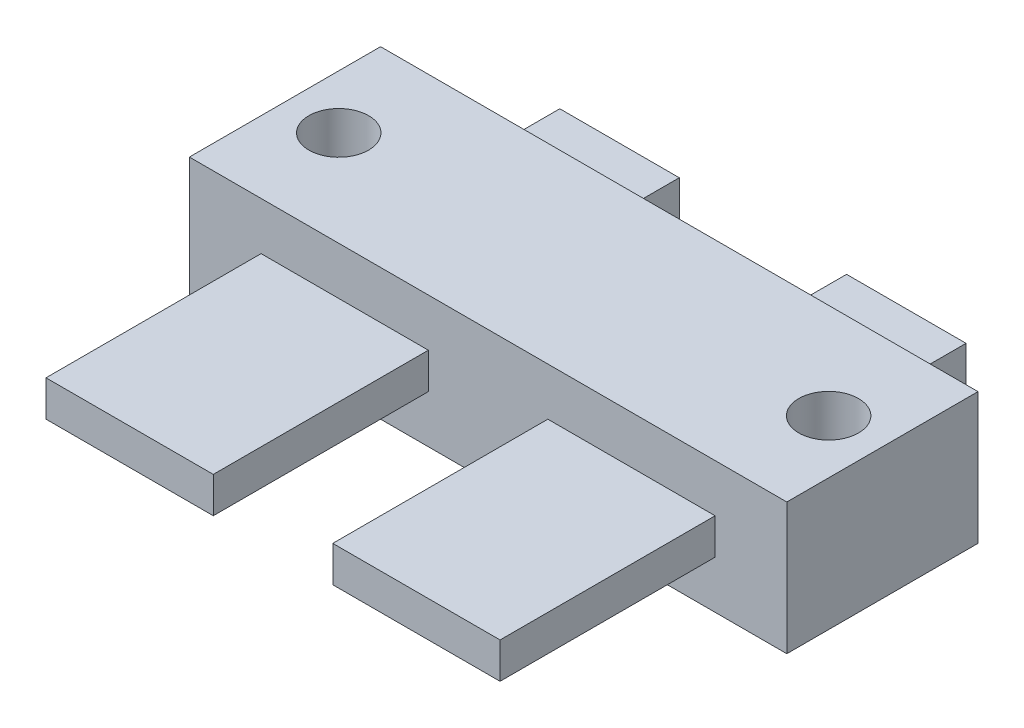
SolidWorks part; units mm, degrees
ref_plane "前视基准面" through (0, 0, 0) normal (0, 0, 1) x (1, 0, 0)
ref_plane "上视基准面" through (0, 0, 0) normal (0, 1, 0) x (1, 0, 0)
ref_plane "右视基准面" through (0, 0, 0) normal (1, 0, 0) x (0, 0, -1)
sketch "草图1" plane through (0, 0, 0) normal (0, 1, 0) x (1, 0, 0)
  line L1 (-12.5, -4) -> (12.5, -4)
  line L2 (-12.5, -4) -> (-12.5, 4)
  line L3 (-12.5, 4) -> (12.5, 4)
  line L4 (12.5, -4) -> (12.5, 4)
  line L5 (-12.5, -4) -> (12.5, 4) construction
  line L6 (-12.5, 4) -> (12.5, -4) construction
  point P0 (0, 0)
  dimension "D1" = 25
  dimension "D2" = 8
extrude "凸台-拉伸1" add sketch "草图1" along normal blind 5.5
sketch "草图3" plane through (0, 0, 4) normal (0, 0, 1) x (1, 0, 0)
  line L0 (-12.5, 5.5) -> (12.5, 5.5) construction
  line L1 (-9.5, 3.5) -> (-2.5, 3.5)
  line L2 (-9.5, 3.5) -> (-9.5, 2)
  line L3 (-9.5, 2) -> (-2.5, 2)
  line L4 (-2.5, 3.5) -> (-2.5, 2)
  line L5 (-9.5, 3.5) -> (-2.5, 2) construction
  line L6 (-9.5, 2) -> (-2.5, 3.5) construction
  line L7 (-12.5, 0) -> (12.5, 0) construction
  line L8 (-12.5, 5.5) -> (-12.5, 0) construction
  line L9 (0, -1000) -> (0, 49000) construction
  line L10 (9.5, 2) -> (2.5, 2)
  line L11 (2.5, 3.5) -> (2.5, 2)
  line L12 (9.5, 3.5) -> (2.5, 3.5)
  line L13 (9.5, 3.5) -> (9.5, 2)
  point P0 (-6, 2.75)
  dimension "D1" = 2
  dimension "D2" = 2
  dimension "D3" = 3
  dimension "D4" = 7
extrude "凸台-拉伸3" add sketch "草图3" along normal blind 9
sketch "草图4" plane through (0, 0, -4) normal (0, 0, -1) x (-1, 0, 0)
  line L0 (-12.5, 5.5) -> (12.5, 5.5) construction
  line L1 (-8.5, 3.5) -> (-3.5, 3.5)
  line L2 (-8.5, 3.5) -> (-8.5, 2)
  line L3 (-8.5, 2) -> (-3.5, 2)
  line L4 (-3.5, 3.5) -> (-3.5, 2)
  line L5 (-8.5, 3.5) -> (-3.5, 2) construction
  line L6 (-8.5, 2) -> (-3.5, 3.5) construction
  line L7 (-12.5, 0) -> (12.5, 0) construction
  line L8 (-12.5, 5.5) -> (-12.5, 0) construction
  line L9 (0, -1000) -> (0, 49000) construction
  line L10 (8.5, 2) -> (3.5, 2)
  line L11 (3.5, 3.5) -> (3.5, 2)
  line L12 (8.5, 3.5) -> (3.5, 3.5)
  line L13 (8.5, 3.5) -> (8.5, 2)
  point P0 (-6, 2.75)
  dimension "D1" = 2
  dimension "D2" = 2
  dimension "D3" = 4
  dimension "D4" = 5
extrude "凸台-拉伸4" add sketch "草图4" along normal blind 3.5
sketch "草图5" plane through (0, 5.5, 0) normal (0, 1, 0) x (1, 0, 0)
  line L0 (-12.5, 4) -> (-12.5, -4) construction
  line L2 (0, 0) -> (50000, 0) construction
  line L3 (0, 0) -> (0, 50000) construction
  circle A0 centre (-10.25, 0) radius 1.25
  circle A2 centre (10.25, 0) radius 1.25
  dimension "D1" = 2.5
  dimension "D2" = 2.25
extrude "切除-拉伸1" cut sketch "草图5" against normal blind 2
